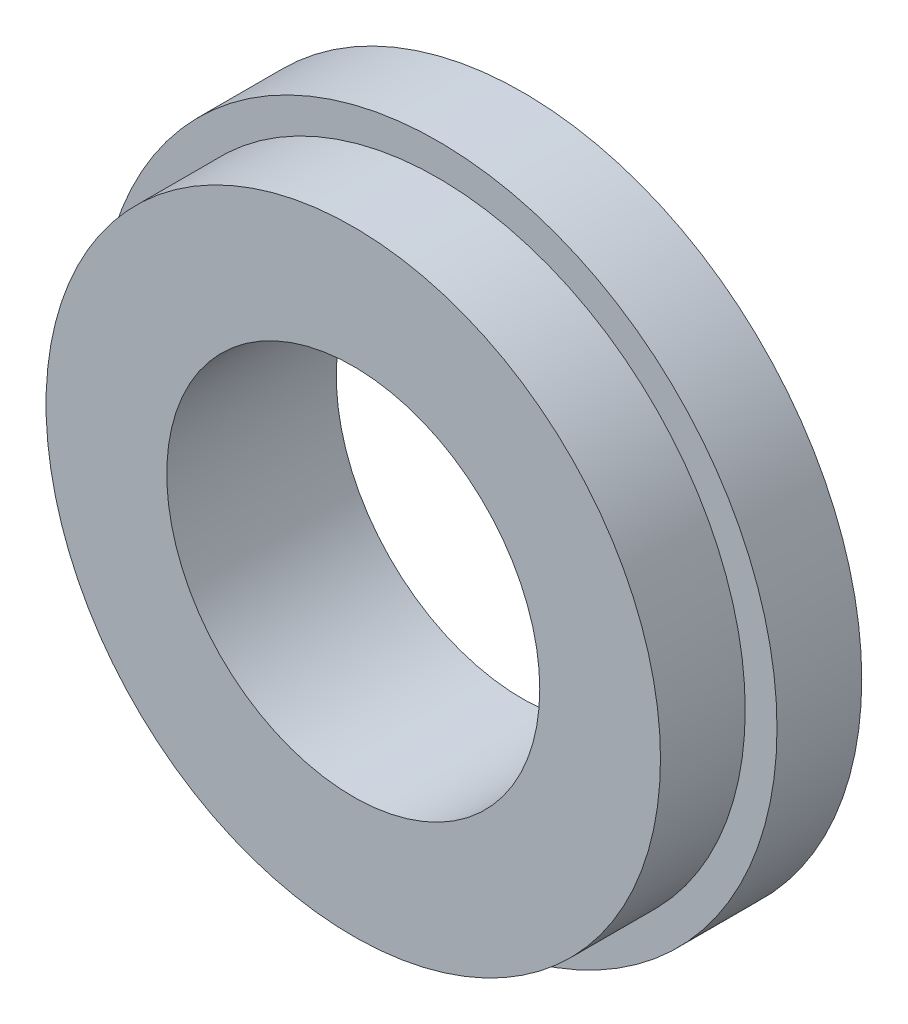
SolidWorks part; units mm, degrees
ref_plane "Front Plane" through (0, 0, 0) normal (0, 0, 1) x (1, 0, 0)
ref_plane "Top Plane" through (0, 0, 0) normal (0, 1, 0) x (1, 0, 0)
ref_plane "Right Plane" through (0, 0, 0) normal (1, 0, 0) x (0, 0, -1)
sketch "Sketch1" plane through (0, 0, 0) normal (1, 0, 0) x (0, 0, -1)
  line L0 (12.7, 46.0375) -> (12.7, 27.9486)
  line L1 (0, 0) -> (12.7, 0) construction
  line L2 (0, 0) -> (0, 46.0375) construction
  line L3 (0, 46.0375) -> (12.7, 46.0375) construction
  line L4 (12.7, 0) -> (12.7, 27.9486) construction
  line L5 (0, 27.9486) -> (12.7, 27.9486)
  line L6 (0, 27.9486) -> (0, 46.0375)
  line L7 (0, 46.0375) -> (12.7, 46.0375)
  line L9 (12.7, 27.9486) -> (25.4, 27.9486)
  line L10 (12.7, 46.0375) -> (12.7, 50.8)
  line L11 (12.7, 50.8) -> (25.4, 50.8)
  line L12 (25.4, 27.9486) -> (25.4, 50.8)
  dimension "D1" = 50.8
  dimension "D2" = 46.0375
  dimension "D3" = 12.7
  dimension "D4" = 12.7
revolve "Revolve1" add sketch "Sketch1" angle 360 about L1
